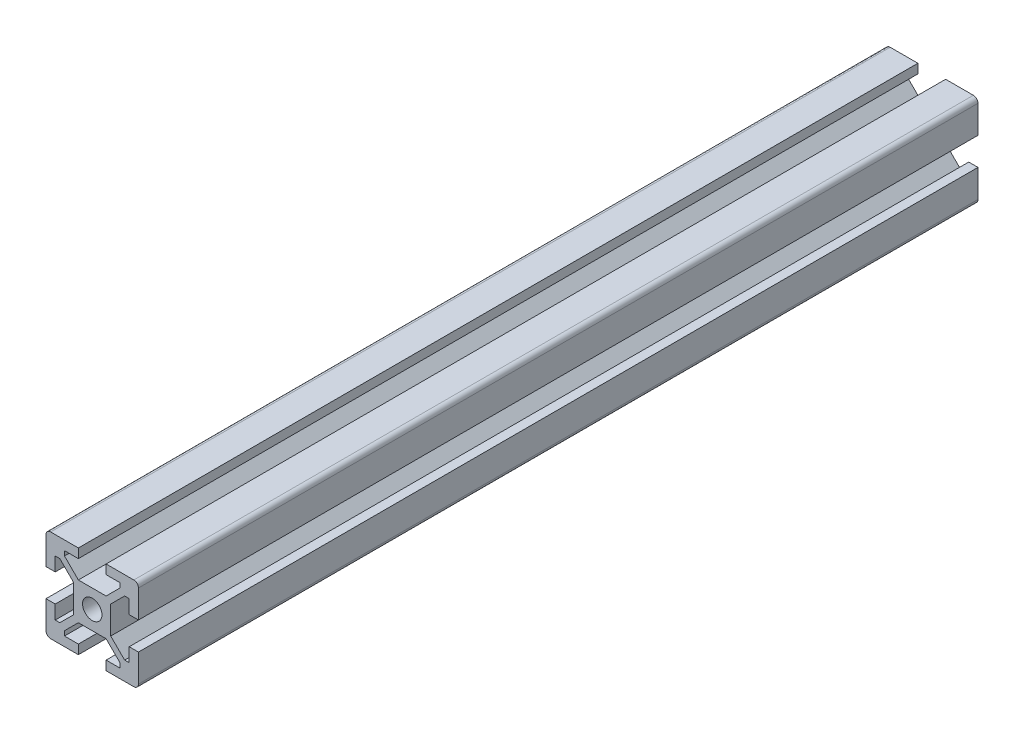
SolidWorks part; units mm, degrees
material "6061 Alloy"
ref_plane "Front Plane" through (0, 0, 0) normal (0, 0, 1) x (1, 0, 0)
ref_plane "Top Plane" through (0, 0, 0) normal (0, 1, 0) x (1, 0, 0)
ref_plane "Right Plane" through (0, 0, 0) normal (1, 0, 0) x (0, 0, -1)
ref_plane "Plane1" through (0, 0, 0) normal (0, 0, -1) x (-1, 0, 0)
sketch "Sketch1" plane through (0, 0, 0) normal (0, 0, -1) x (-1, 0, 0)
  line L0 (6, -8) -> (3, -8)
  line L1 (3, -8) -> (3, -10)
  line L2 (3, -10) -> (9, -10)
  line L3 (10, -9) -> (10, -3)
  line L4 (10, -3) -> (8, -3)
  line L5 (8, -3) -> (8, -6)
  line L6 (8, -6) -> (7, -6)
  line L7 (7, -6) -> (4, -3)
  line L8 (4, -3) -> (4, 3)
  line L9 (4, 3) -> (7, 6)
  line L10 (7, 6) -> (8, 6)
  line L11 (8, 6) -> (8, 3)
  line L12 (8, 3) -> (10, 3)
  line L13 (10, 3) -> (10, 9)
  line L14 (9, 10) -> (3, 10)
  line L15 (3, 10) -> (3, 8)
  line L16 (3, 8) -> (6, 8)
  line L17 (6, 8) -> (6, 7)
  line L18 (6, 7) -> (3, 4)
  line L19 (3, 4) -> (-3, 4)
  line L20 (-3, 4) -> (-6, 7)
  line L21 (-6, 7) -> (-6, 8)
  line L22 (-6, 8) -> (-3, 8)
  line L23 (-3, 8) -> (-3, 10)
  line L24 (-3, 10) -> (-9, 10)
  line L25 (-10, 9) -> (-10, 3)
  line L26 (-10, 3) -> (-8, 3)
  line L27 (-8, 3) -> (-8, 6)
  line L28 (-8, 6) -> (-7, 6)
  line L29 (-7, 6) -> (-4, 3)
  line L30 (-4, 3) -> (-4, -3)
  line L31 (-4, -3) -> (-7, -6)
  line L32 (-7, -6) -> (-8, -6)
  line L33 (-8, -6) -> (-8, -3)
  line L34 (-8, -3) -> (-10, -3)
  line L35 (-10, -3) -> (-10, -9)
  line L36 (-9, -10) -> (-3, -10)
  line L37 (-3, -10) -> (-3, -8)
  line L38 (-3, -8) -> (-6, -8)
  line L39 (-6, -8) -> (-6, -7)
  line L40 (-6, -7) -> (-3, -4)
  line L41 (-3, -4) -> (3, -4)
  line L42 (3, -4) -> (6, -7)
  line L43 (6, -7) -> (6, -8)
  line L44 (0, 4) -> (0, 0) construction
  line L45 (0, 0) -> (-4, 0) construction
  line L46 (0, 0) -> (4, 0) construction
  line L47 (0, 0) -> (0, -4) construction
  circle A0 centre (0, 0) radius 2.1
  arc A1 (9, -10) -> (10, -9) centre (9, -9) ccw
  arc A2 (10, 9) -> (9, 10) centre (9, 9) ccw
  arc A3 (-9, 10) -> (-10, 9) centre (-9, 9) ccw
  arc A4 (-10, -9) -> (-9, -10) centre (-9, -9) ccw
  dimension "D6" = 1
  dimension "D10" = 4.2
  dimension "D1" = 10
  dimension "D2" = 10
  dimension "D3" = 10
  dimension "D4" = 10
  dimension "D5" = 8
  dimension "D7" = 2
  dimension "D8" = 7
  dimension "D9" = 8
  dimension "D11" = 1
  dimension "D12" = 1
  dimension "D13" = 2
  dimension "D14" = 3
  dimension "D15" = 2
  dimension "D16" = 1
  dimension "D17" = 1
  dimension "D18" = 4.2426
  dimension "D19" = 6
  dimension "D20" = 7
extrude "Boss-Extrude1" add sketch "Sketch1" against normal blind 181.575
ref_plane "Plane2" through (0, 0, 0) normal (1, 0, 0) x (0, 0, -1)
sketch "Sketch2" plane through (0, 10, 0) normal (0, 1, 0) x (1, 0, 0)
  line L0 (0, -3.3) -> (0, 3.3) construction
  line L1 (0, -175.9786) -> (0, -162.307) construction
  circle A0 centre (0, -175.9786) radius 3
